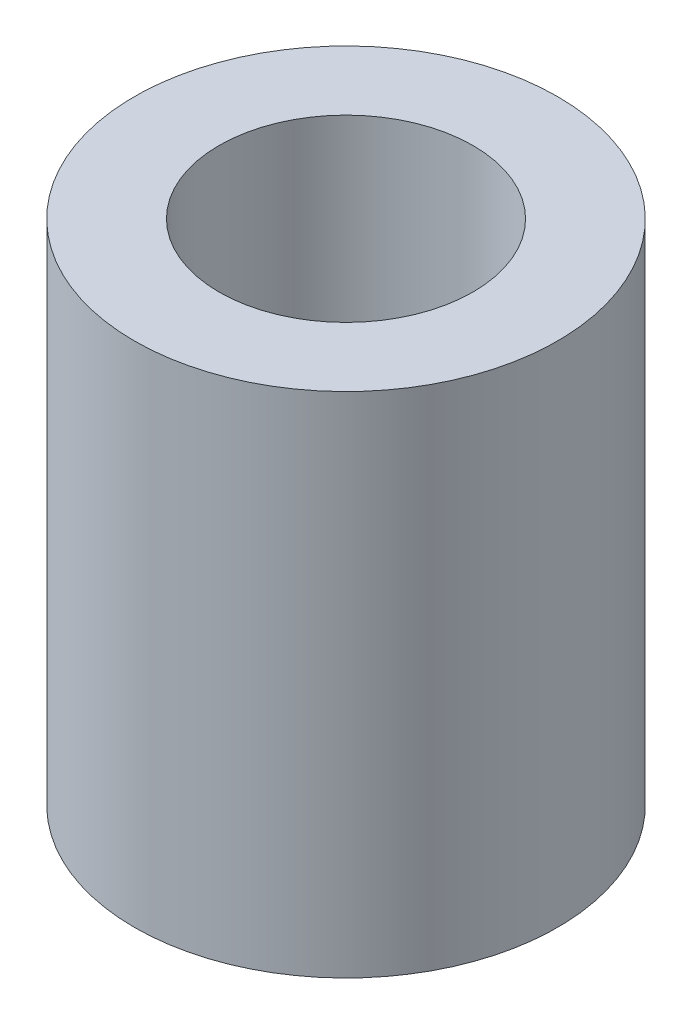
SolidWorks part; units mm, degrees
ref_plane "前视基准面" through (0, 0, 0) normal (0, 0, 1) x (1, 0, 0)
ref_plane "上视基准面" through (0, 0, 0) normal (0, 1, 0) x (1, 0, 0)
ref_plane "右视基准面" through (0, 0, 0) normal (1, 0, 0) x (0, 0, -1)
sketch "草图4" plane through (0, 0, 0) normal (0, 1, 0) x (1, 0, 0)
  circle A0 centre (0, 0) radius 5
  circle A1 centre (0, 0) radius 3
extrude "凸台-拉伸3" add sketch "草图4" along normal blind 10
sketch "草图5" plane through (0, 0, 0) normal (0, -1, 0) x (1, 0, 0)
  circle A0 centre (0, 0) radius 5
extrude "凸台-拉伸5" add sketch "草图5" along normal blind 2
